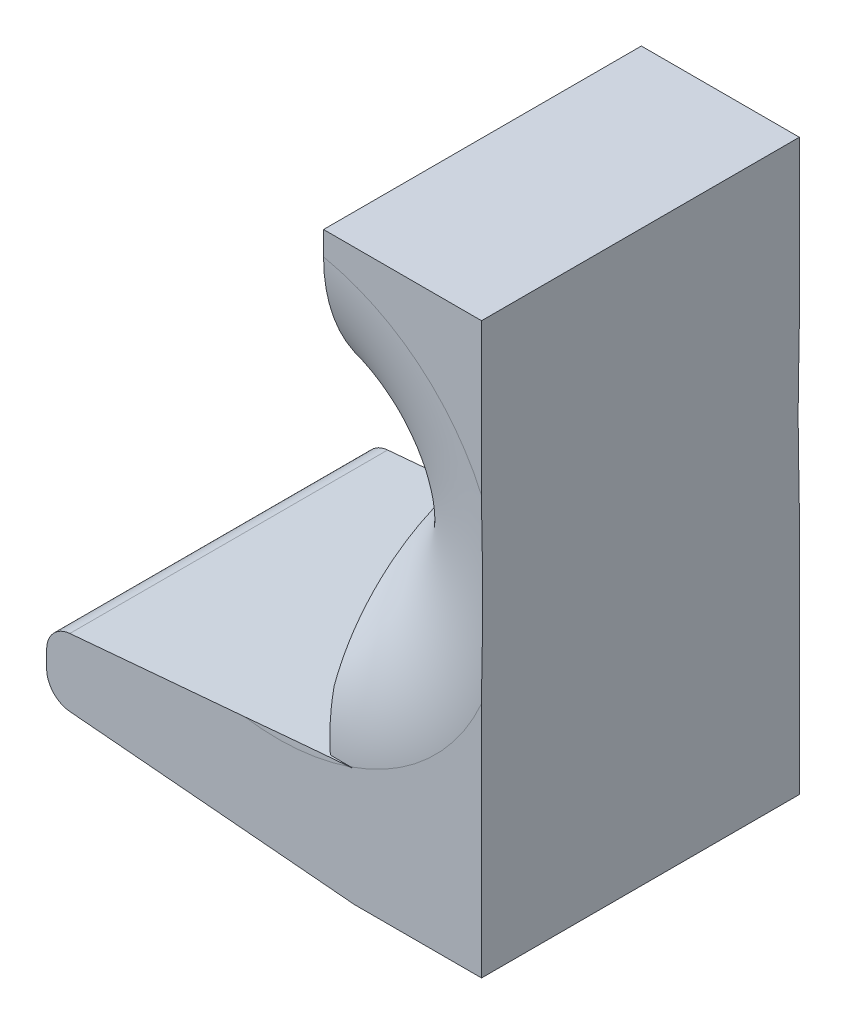
SolidWorks part; units mm, degrees
ref_plane "Front Plane" through (0, 0, 0) normal (0, 0, 1) x (1, 0, 0)
ref_plane "Top Plane" through (0, 0, 0) normal (0, 1, 0) x (1, 0, 0)
ref_plane "Right Plane" through (0, 0, 0) normal (1, 0, 0) x (0, 0, -1)
sketch "finger" plane through (0, 0, 0) normal (0, 0, 1) x (1, 0, 0)
  line L0 (0, 0) -> (5.0161, 13.7815) construction
  line L1 (5.0161, 13.7815) -> (5.0161, 28.518) construction
  line L2 (0, 0) -> (-4.3003, -49.1522)
  line L3 (-4.3003, -49.1522) -> (16.1455, -66.3082)
  line L4 (16.1455, -66.3082) -> (32.8367, -61.8359)
  line L5 (31.6073, -57.2477) -> (14.9161, -61.7201)
  line L6 (13.6867, -57.132) -> (30.3779, -52.6596)
  line L7 (13.6867, -57.132) -> (14.9161, -61.7201)
  line L8 (14.9161, -61.7201) -> (16.1455, -66.3082)
  line L9 (31.6073, -57.2477) -> (36.1954, -56.0183) construction
  circle A0 centre (31.6073, -57.2477) radius 4.75
  dimension "D3" = 15
  dimension "D4" = 55
  dimension "D5" = 20
  dimension "D6" = 55
  dimension "D7" = 49.34
  dimension "D8" = 26.69
  dimension "D2" = 9.5
  dimension "D1" = 22.03
ref_plane "est_lift_plane" through (31.6073, 0, 0) normal (1, 0, 0) x (0, 0, -1)
sketch "Sketch2" plane through (0, 0, 0) normal (0, 0, 1) x (1, 0, 0)
  line L0 (30.3573, -46.4977) -> (30.3573, -43.4977) construction
  line L1 (30.3573, -43.4977) -> (30.3573, -42.9977) construction
  line L2 (30.3573, -46.4977) -> (30.3573, -46.3977) construction
  line L3 (30.3573, -46.3977) -> (30.3573, -46.3727) construction
  line L4 (33.928, -51.4977) -> (36.3573, -51.4977) construction
  line L5 (30.3573, -47.9977) -> (36.3573, -47.9977) construction
  line L6 (30.3573, -52.4977) -> (36.3573, -52.4977) construction
  line L7 (33.928, -51.4977) -> (33.928, -52.4977)
  line L8 (33.928, -51.4977) -> (33.928, -28.9977)
  line L9 (33.928, -28.9977) -> (46.3573, -28.9977)
  line L10 (46.3573, -28.9977) -> (46.3573, -73.7765)
  line L12 (12.1455, -71.6582) -> (12.1455, -66.6582)
  line L13 (12.1455, -66.6582) -> (36.3573, -64.5399)
  line L14 (36.3573, -64.5399) -> (36.3573, -52.4977)
  line L15 (16.1455, -66.3082) -> (16.1455, -72.0082)
  line L16 (12.1455, -69.1582) -> (16.1455, -69.1582)
  line L17 (30.3573, -46.4977) -> (30.3573, -46.3727) construction
  line L18 (1.0853, 18.3368) -> (13.5146, 18.3368) construction
  line L19 (-25.8903, -11.4233) -> (-21.8903, -11.4233) construction
  line L20 (-25.8903, -13.9233) -> (-25.8903, -8.9233) construction
  line L21 (-2.4854, 5.3476) -> (3.5146, 5.3476) construction
  line L22 (1.0853, 1.8476) -> (3.5146, 1.8476) construction
  line L23 (33.928, -52.4977) -> (33.928, -64.9977) construction
  line L24 (30.3573, -47.9977) -> (30.3573, -64.9977) construction
  line L25 (30.3573, -47.9977) -> (30.3573, -30.9977) construction
  line L26 (30.3573, -30.9977) -> (30.3573, -28.9977) construction
  line L27 (-2.4854, 18.3368) -> (-2.4854, 16.3368) construction
  line L28 (33.928, -52.4977) -> (36.3573, -52.4977)
  line L30 (12.1455, -71.6582) -> (36.3573, -73.7765)
  line L34 (36.3573, -73.7765) -> (46.3573, -73.7765)
  line L35 (0, 0) -> (6, 0) construction
  line L37 (3.5707, -3.5) -> (3.5707, -4.5) construction
  line L38 (-23.405, -20.4436) -> (-23.405, -15.4436) construction
  line L39 (-23.405, -17.9436) -> (-19.405, -17.9436) construction
  line L40 (0, 12.8193) -> (0, 10.8193) construction
  circle A0 centre (30.3573, -47.9977) radius 5 construction
  circle A1 centre (30.3573, -47.9977) radius 4.5 construction
  circle A2 centre (30.3573, -47.9977) radius 1.5 construction
  circle A3 centre (30.3573, -47.9977) radius 1.6 construction
  circle A4 centre (30.3573, -47.9977) radius 1.625 construction
  circle A5 centre (-2.4854, 5.3476) radius 5 construction
  circle A6 centre (-2.4854, 5.3476) radius 4.5 construction
  circle A7 centre (-2.4854, 5.3476) radius 1.625 construction
  circle A9 centre (0, 0) radius 5 construction
  circle A10 centre (-2.4854, 5.3476) radius 1.6 construction
  circle A11 centre (-2.4854, 5.3476) radius 1.5 construction
  circle A12 centre (31.6073, -57.2477) radius 4.75 construction
  circle A13 centre (0, 0) radius 4.5 construction
  dimension "D2" = 5
  dimension "D1" = 12.5
  dimension "D3" = 10
extrude "Boss-Extrude1" add sketch "Sketch2" along normal mid plane 25
sketch "Sketch4" plane through (36.3573, 0, 0) normal (-1, 0, 0) x (0, 0, 1)
  line L0 (0, -27.8616) -> (0, 27.8616) construction
  line L1 (-12.5, -64.9977) -> (-12.5, -52.4977)
  line L2 (-12.5, -52.4977) -> (12.5, -52.4977)
  line L3 (12.5, -52.4977) -> (12.5, -64.9977)
  circle A0 centre (0, -64.9977) radius 12.5 construction
  arc A1 (-12.5, -64.9977) -> (12.5, -64.9977) centre (0, -64.9977) cw
  line M4 (-12.5, -52.4977) -> (-12.5, -64.5399)
  line M6 (12.5, -64.5399) -> (12.5, -52.4977)
  line M7 (12.5, -52.4977) -> (-12.5, -52.4977)
extrude "Boss-Extrude2" add sketch "Sketch4" along normal up to surface (2.4293 mm away) contours A1 L2 M4 | A1 M7 M6
ref_plane "roller_plane" through (30.3573, 0, 0) normal (-1, 0, 0) x (0, 0, 1)
sketch "Sketch3" plane through (30.3573, 0, 0) normal (-1, 0, 0) x (0, 0, 1)
  line L0 (0, -27.8616) -> (0, 27.8616) construction
  line L1 (0, 0) -> (0, -49.1522) construction
  line L2 (-12.5, -47.9977) -> (12.5, -47.9977)
  line L3 (-12.5, -64.5399) -> (-12.5, -28.9977) construction
  line L4 (12.5, -28.9977) -> (12.5, -64.5399) construction
  line L5 (-12.5, -47.9977) -> (-12.5, -30.4977)
  line L6 (12.5, -47.9977) -> (12.5, -30.4977)
  circle A0 centre (0, -30.4977) radius 12.5 construction
  arc A1 (-12.5, -30.4977) -> (12.5, -30.4977) centre (0, -30.4977) ccw
revolve "Cut-Revolve1" cut sketch "Sketch3" angle 360 about L2
fillet "Fillet2" radius 2 2 edges at (12.1455, -66.6582, 0) (12.1455, -71.6582, 0)
equation "\"depth\"= 8.5"
equation "\"width\"=25"
equation "\"distal\"= 22.03"
equation "\"proximal\"= 49.34"
equation "\"medial\"= 26.69"
equation "\"h_offset\"= 0"
equation "\"l_offset\"= 0"
equation "\"D7@finger\" = \"proximal\""
equation "\"D8@finger\" = \"medial\""
equation "\"D1@Boss-Extrude1\"=\"width\""
equation "\"D1@finger\"=\"distal\""
equation "\"D1@Sketch2\"=\"width\"/2"
